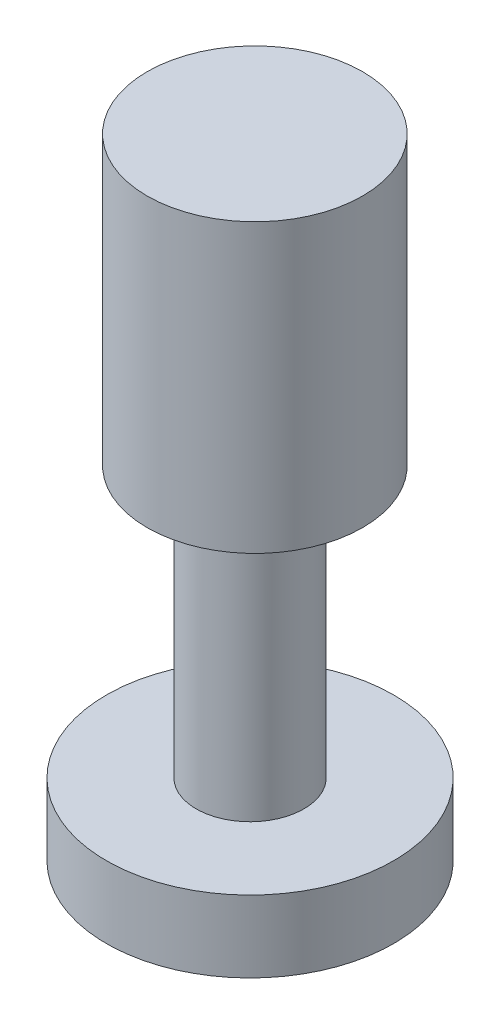
SolidWorks part; units mm, degrees
ref_plane "Front Plane" through (0, 0, 0) normal (0, 0, 1) x (1, 0, 0)
ref_plane "Top Plane" through (0, 0, 0) normal (0, 1, 0) x (1, 0, 0)
ref_plane "Right Plane" through (0, 0, 0) normal (1, 0, 0) x (0, 0, -1)
sketch "Sketch1" plane through (0, 0, 0) normal (0, 1, 0) x (1, 0, 0)
  circle A0 centre (0, 0) radius 7.5
  dimension "D1" = 15
extrude "Boss-Extrude1" add sketch "Sketch1" along normal blind 38
sketch "Sketch2" plane through (0, 0, 0) normal (0, -1, 0) x (1, 0, 0)
  circle A0 centre (0, 0) radius 20
  dimension "D1" = 40
extrude "Boss-Extrude2" add sketch "Sketch2" along normal blind 10 contours A0
sketch "Sketch3" plane through (0, 38, 0) normal (0, 1, 0) x (1, 0, 0)
  circle A0 centre (0.6704, 0) radius 15
  dimension "D1" = 30
extrude "Boss-Extrude3" add sketch "Sketch3" along normal blind 40
